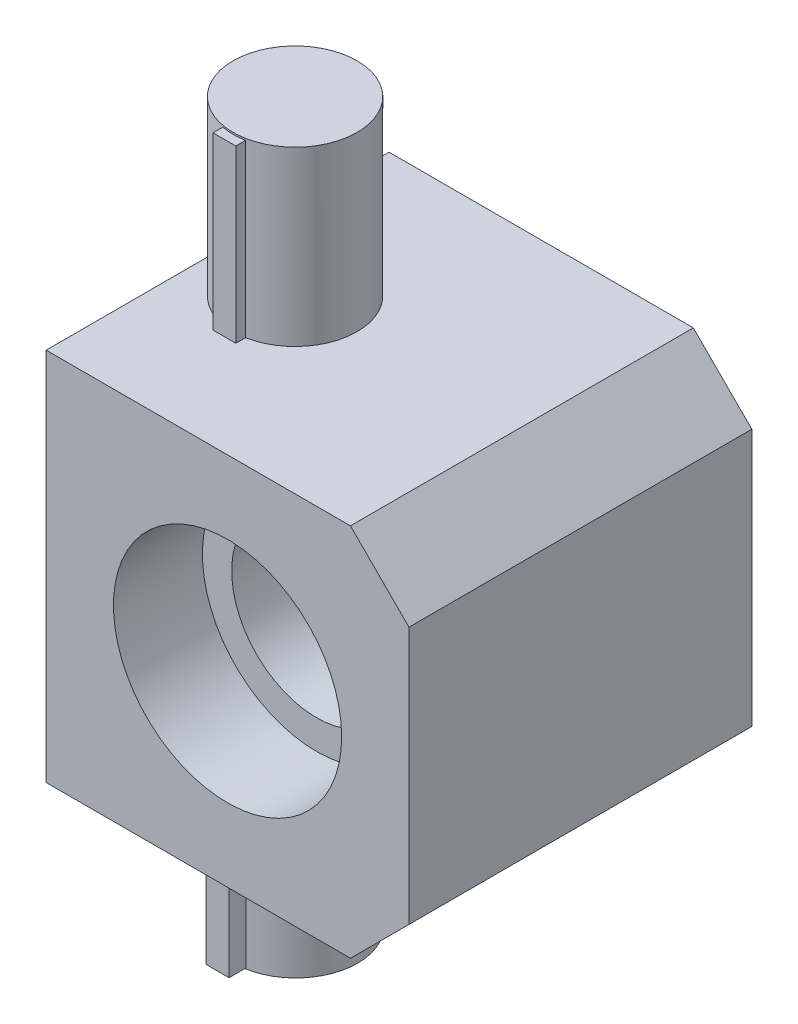
SolidWorks part; units mm, degrees
ref_plane "Front Plane" through (0, 0, 0) normal (0, 0, 1) x (1, 0, 0)
ref_plane "Top Plane" through (0, 0, 0) normal (0, 1, 0) x (1, 0, 0)
ref_plane "Right Plane" through (0, 0, 0) normal (1, 0, 0) x (0, 0, -1)
sketch "Sketch2" plane through (0, 0, 0) normal (0, 0, 1) x (1, 0, 0)
  line L1 (3.1, 3.2) -> (-3.1, 3.2)
  line L2 (3.1, 3.2) -> (3.1, -3.2)
  line L3 (3.1, -3.2) -> (-3.1, -3.2)
  line L4 (-3.1, 3.2) -> (-3.1, -3.2)
  line L5 (3.1, 3.2) -> (-3.1, -3.2) construction
  line L6 (3.1, -3.2) -> (-3.1, 3.2) construction
  point P0 (0, 0)
  dimension "D1" = 6.2
  dimension "D2" = 6.4
extrude "Boss-Extrude1" add sketch "Sketch2" along normal blind 5.86
chamfer "Chamfer1" distance 1 angle 45 2 edges at (3.1, 3.2, 2.93) (3.1, -3.2, 2.93)
sketch "Sketch3" plane through (0, 0, 0) normal (0, 0, -1) x (-1, 0, 0)
  circle A0 centre (0, 0) radius 1.7
  circle A1 centre (0, 0) radius 1.45
  dimension "D1" = 3.4
  dimension "D2" = 2.9
sketch "Sketch5" plane through (0, 0, 5.86) normal (0, 0, 1) x (1, 0, 0)
  circle A0 centre (0, 0) radius 1.95
  dimension "D1" = 3.9
extrude "Cut-Extrude3" cut sketch "Sketch5" against normal blind 1.52
sketch "Sketch6" plane through (0, 0, 4.34) normal (0, 0, 1) x (1, 0, 0)
  circle A0 centre (0, 0) radius 1.45
  dimension "D1" = 2.9
extrude "Cut-Extrude4" cut sketch "Sketch6" against normal through all
sketch "Sketch7" plane through (0, 3.2, 0) normal (0, 1, 0) x (1, 0, 0)
  line L0 (-3.1, -2.93) -> (2.1, -2.93) construction
  line L1 (-3.1, -5.86) -> (-3.1, 0) construction
  line L2 (2.1, -5.86) -> (2.1, 0) construction
  line L3 (2.1, -2.93) -> (-3.1, -2.93) construction
  line L4 (2.1, -5.86) -> (-1.776, -5.86)
  line L5 (2.1, -5.86) -> (-3.1, -5.86) construction
  circle A0 centre (-1.776, -2.93) radius 1.06
  dimension "D1" = 2.12
extrude "Boss-Extrude2" add sketch "Sketch7" along normal blind 2.95 contours A0
sketch "Sketch8" plane through (0, 3.2, 0) normal (0, 1, 0) x (1, 0, 0)
  line L1 (-1.971, -3.8424) -> (-1.581, -3.8424)
  line L2 (-1.971, -3.8424) -> (-1.971, -4.1376)
  line L3 (-1.971, -4.1376) -> (-1.581, -4.1376)
  line L4 (-1.581, -3.8424) -> (-1.581, -4.1376)
  line L5 (-1.971, -3.8424) -> (-1.581, -4.1376) construction
  line L6 (-1.971, -4.1376) -> (-1.581, -3.8424) construction
  circle A0 centre (-1.776, -2.93) radius 1.06 construction
  point P0 (-1.776, -3.99)
  dimension "D1" = 0.39
extrude "Boss-Extrude3" add sketch "Sketch8" along normal blind 2.92
sketch "Sketch9" plane through (0, -3.2, 0) normal (0, -1, 0) x (1, 0, 0)
  line L0 (-0.5, 5.86) -> (-0.5, 0) construction
  line L1 (-3.1, 5.86) -> (2.1, 5.86) construction
  line L2 (-3.1, 0) -> (2.1, 0) construction
  line L3 (-3.1, 2.93) -> (2.1, 2.93) construction
  line L4 (-3.1, 5.86) -> (-3.1, 0) construction
  line L5 (2.1, 0) -> (2.1, 5.86) construction
  line L6 (2.1, 0) -> (-1.7767, 0)
  circle A0 centre (-1.7641, 2.9308) radius 1.06
  dimension "D1" = 2.12
extrude "Boss-Extrude4" add sketch "Sketch9" along normal blind 2.94 contours A0
sketch "Sketch11" plane through (0, -3.2, 0) normal (0, -1, 0) x (1, 0, 0)
  line L2 (-1.5691, 3.7156) -> (-1.9591, 3.7156)
  line L3 (-1.5691, 3.7156) -> (-1.5691, 4.266)
  line L4 (-1.5691, 4.266) -> (-1.9591, 4.266)
  line L5 (-1.9591, 3.7156) -> (-1.9591, 4.266)
  line L6 (-1.5691, 3.7156) -> (-1.9591, 4.266) construction
  line L7 (-1.5691, 4.266) -> (-1.9591, 3.7156) construction
  dimension "D1" = 0.39
extrude "Boss-Extrude5" add sketch "Sketch11" along normal blind 2.92 contours L3 L2 L5 L4
